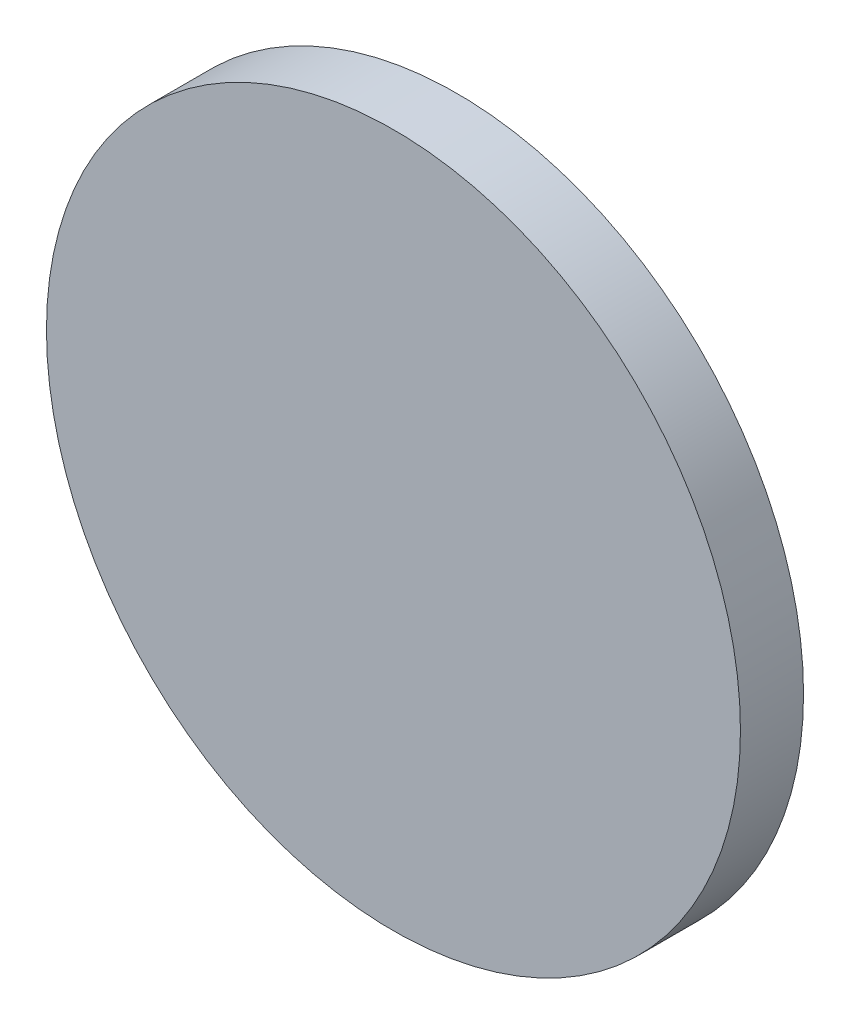
SolidWorks part; units mm, degrees
material "Vidrio"
ref_plane "Alzado" through (0, 0, 0) normal (0, 0, 1) x (1, 0, 0)
ref_plane "Planta" through (0, 0, 0) normal (0, 1, 0) x (1, 0, 0)
ref_plane "Vista lateral" through (0, 0, 0) normal (1, 0, 0) x (0, 0, -1)
sketch "Croquis1" plane through (0, 0, 0) normal (0, 0, 1) x (1, 0, 0)
  circle A0 centre (0, 0) radius 11
  dimension "D1" = 22
extrude "Saliente-Extruir1" add sketch "Croquis1" along normal blind 2
